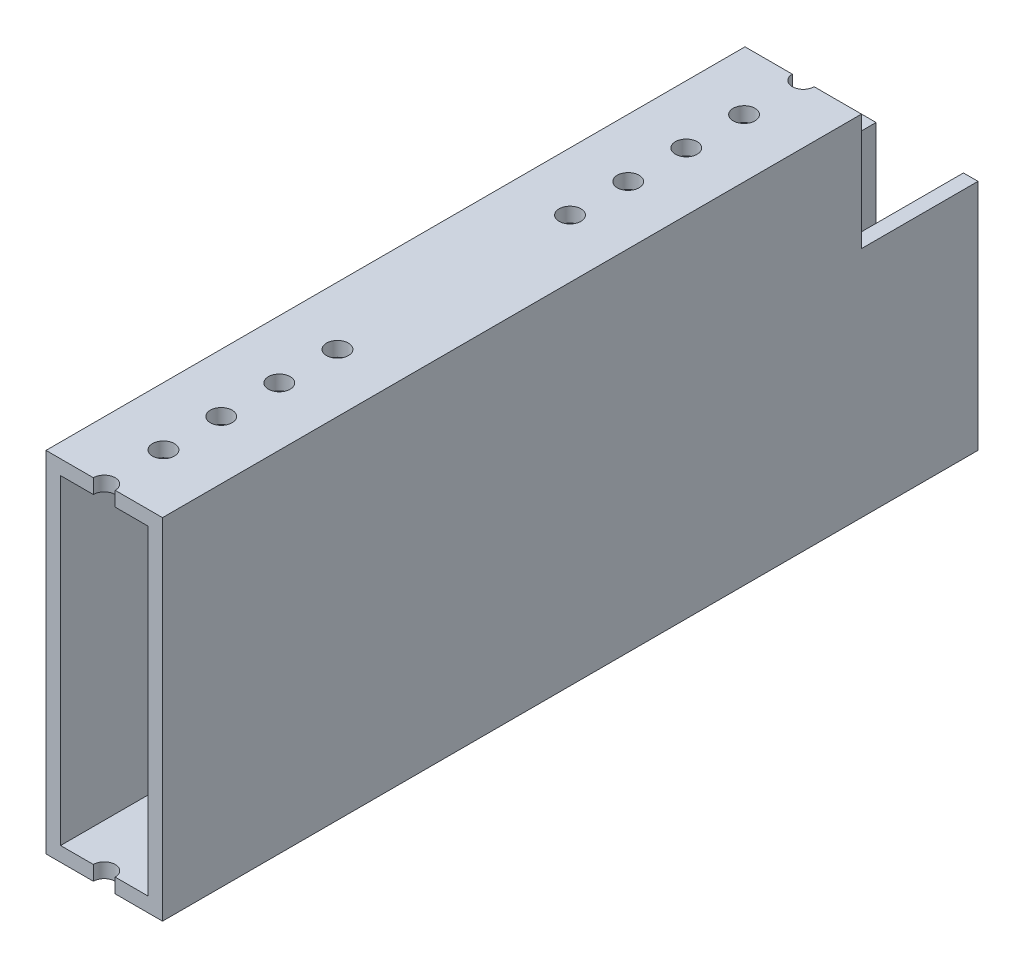
SolidWorks part; units mm, degrees
ref_plane "Front Plane" through (0, 0, 0) normal (0, 0, 1) x (1, 0, 0)
ref_plane "Top Plane" through (0, 0, 0) normal (0, 1, 0) x (1, 0, 0)
ref_plane "Right Plane" through (0, 0, 0) normal (1, 0, 0) x (0, 0, -1)
sketch "Sketch1" plane through (0, 0, 0) normal (0, 0, 1) x (1, 0, 0)
  line L1 (-12.7, -38.1) -> (12.7, -38.1)
  line L2 (-12.7, -38.1) -> (-12.7, 38.1)
  line L3 (-12.7, 38.1) -> (12.7, 38.1)
  line L4 (12.7, -38.1) -> (12.7, 38.1)
  line L5 (-12.7, -38.1) -> (12.7, 38.1) construction
  line L6 (-12.7, 38.1) -> (12.7, -38.1) construction
  point P0 (0, 0)
  dimension "D1" = 25.4
  dimension "D2" = 76.2
extrude "Boss-Extrude1" add sketch "Sketch1" along normal mid plane 177.8
shell "Shell1" thickness 3.175
sketch "Sketch2" plane through (-12.7, 0, 0) normal (-1, 0, 0) x (0, 0, 1)
  line L1 (-88.9, 38.1) -> (-63.5, 38.1)
  line L2 (-88.9, 38.1) -> (-88.9, 12.7)
  line L3 (-88.9, 12.7) -> (-63.5, 12.7)
  line L4 (-63.5, 38.1) -> (-63.5, 12.7)
  dimension "D1" = 25.4
extrude "Cut-Extrude1" cut sketch "Sketch2" against normal through all
sketch "Sketch3" plane through (0, 38.1, 0) normal (0, 1, 0) x (1, 0, 0)
  line L0 (9.525, -88.9) -> (-9.525, -88.9) construction
  line L1 (12.7, -88.9) -> (-12.7, -88.9) construction
  line L2 (-12.7, -88.9) -> (-12.7, 63.5) construction
  line L3 (-20.8214, -12.7) -> (21.7075, -12.7) construction
  circle A0 centre (0, -88.9) radius 2.3812
  circle A1 centre (0, -75.9959) radius 2.3812
  circle A2 centre (0, -63.3973) radius 2.3812
  circle A3 centre (0, -50.7315) radius 2.3812
  circle A4 centre (0, -38.0486) radius 2.3812
  circle A5 centre (0, 63.5) radius 2.3812
  circle A6 centre (0, 12.6486) radius 2.3812
  circle A7 centre (0, 25.3315) radius 2.3812
  circle A8 centre (0, 37.9973) radius 2.3812
  circle A9 centre (0, 50.5959) radius 2.3812
  point P10 (0, -88.9)
  point P15 (-12.7, -12.7)
  dimension "D1" = 4.7625
  dimension "D3" = 12.9041
  dimension "D2" = 0
  dimension "D4" = 25.5027
  dimension "D5" = 38.1685
  dimension "D6" = 50.8514
extrude "Cut-Extrude2" cut sketch "Sketch3" against normal through all
sketch "Sketch4" [suppressed] plane through (0, 38.1, 0) normal (0, 1, 0) x (1, 0, 0)
  line L2 (-12.7, -88.9) -> (-12.7, -12.7)
  line L3 (-12.7, -88.9) -> (-12.7, 63.5) construction
  line L4 (-20.5201, -12.7) -> (22.1381, -12.7) construction
